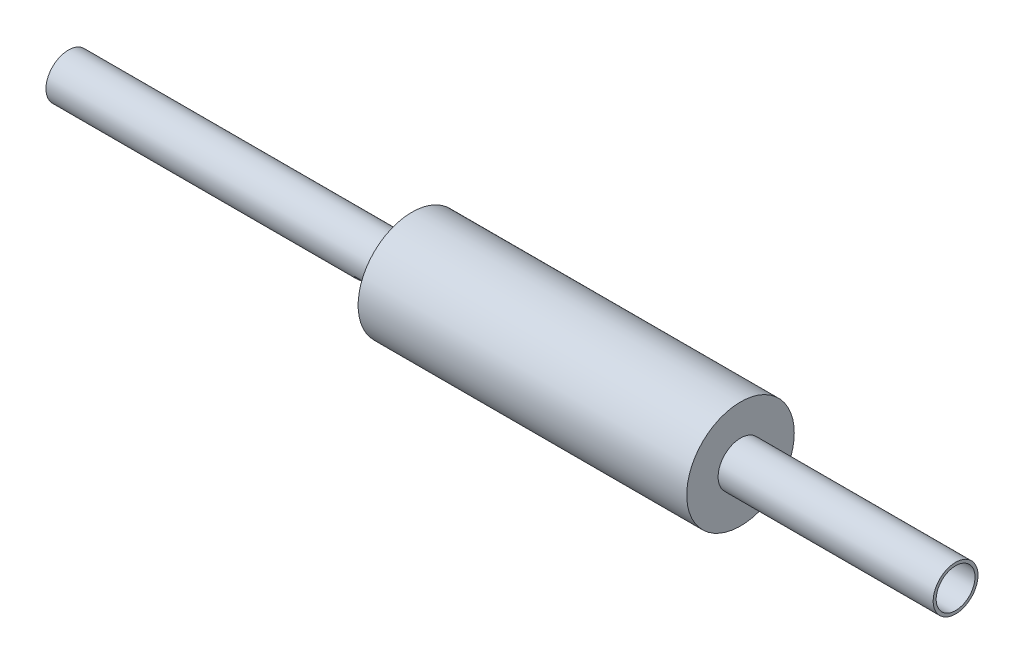
SolidWorks part; units mm, degrees
ref_plane "Front Plane" through (0, 0, 0) normal (0, 0, 1) x (1, 0, 0)
ref_plane "Top Plane" through (0, 0, 0) normal (0, 1, 0) x (1, 0, 0)
ref_plane "Right Plane" through (0, 0, 0) normal (1, 0, 0) x (0, 0, -1)
sketch "Sketch1" plane through (0, 0, 0) normal (0, 0, 1) x (1, 0, 0)
  line L0 (196.3562, 0) -> (-196.3562, 0) construction
  line L3 (127, 7.5) -> (-170, 7.5)
  line L4 (0, -42.6677) -> (0, 42.6677) construction
  line L7 (127, 7.5) -> (127, 0)
  line L8 (127, 0) -> (-127, 0) construction
  line L9 (-170, 7.5) -> (-170, 6.5)
  line L10 (-170, 6.5) -> (-127, 6.5)
  line L11 (-127, 6.5) -> (-127, 0) construction
  line L12 (-55, 18) -> (55, 18)
  line L13 (-55, 18) -> (-55, 7.5)
  line L14 (55, 18) -> (55, 7.5)
  line L15 (-127, 6.5) -> (127, 6.5)
  point P3 (0, 18)
  point P10 (0, 0)
  dimension "D1" = 127
  dimension "D3" = 43
  dimension "D4" = 15
  dimension "D5" = 13
  dimension "D6" = 36
  dimension "D7" = 110
  dimension "D2" = 127
revolve "Revolve1" add sketch "Sketch1" angle 360 about L0
sketch "Sketch2" plane through (0, 0, 0) normal (0, 1, 0) x (1, 0, 0)
  line L0 (127, 0) -> (-127, 0) construction
  line L1 (-68, -6.5) -> (-60, -6.5)
  line L2 (-68, -6.5) -> (-68, 6.5)
  line L3 (-68, 6.5) -> (-60, 6.5)
  line L4 (-60, -6.5) -> (-60, 6.5)
  line L5 (-68, -6.5) -> (-60, 6.5) construction
  line L6 (-68, 6.5) -> (-60, -6.5) construction
  point P0 (-64, 0)
  dimension "D1" = 5
  dimension "D2" = 8
  dimension "D3" = 13
extrude "Cut-Extrude1" cut sketch "Sketch2" against normal up to next
equation "\"D2@Sketch1\"=\"D1@Sketch1\""
